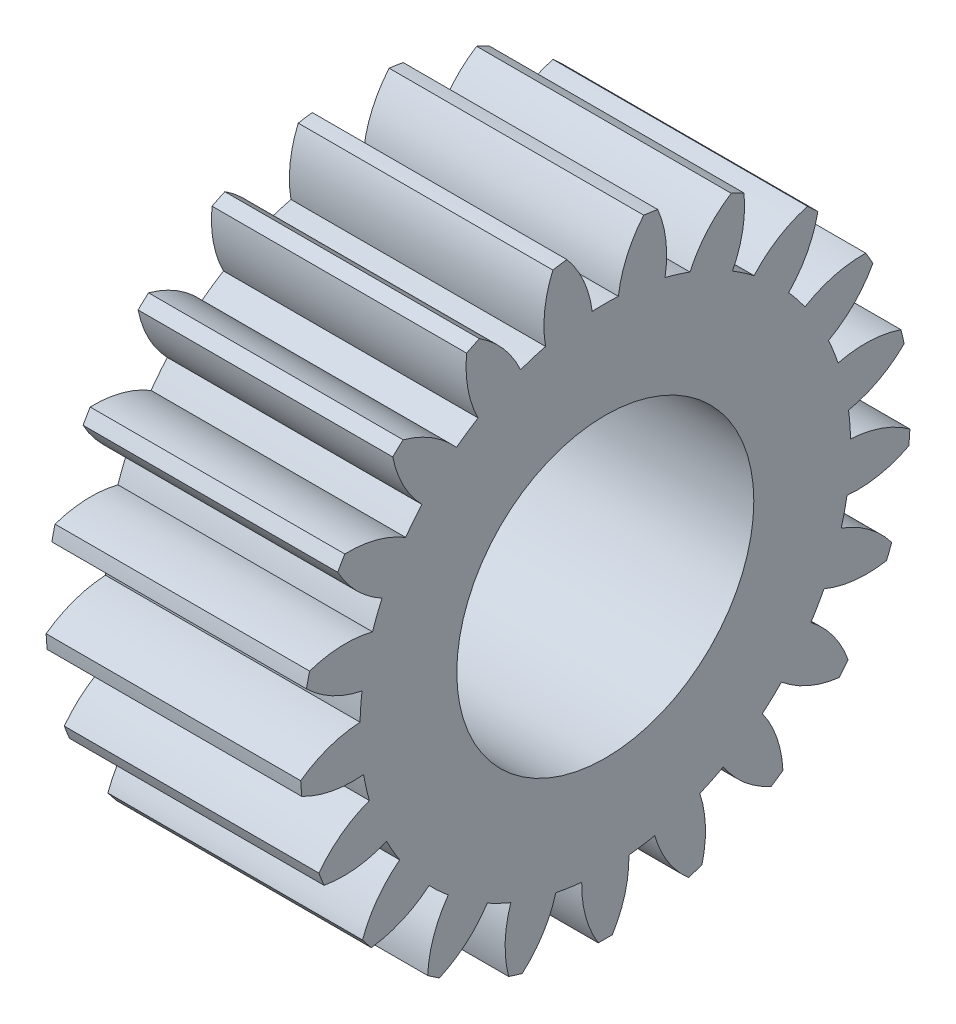
SolidWorks part; units mm, degrees
ref_plane "Plane1" through (0, 0, 0) normal (0, 0, 1) x (1, 0, 0)
ref_plane "Plane2" through (0, 0, 0) normal (0, 1, 0) x (1, 0, 0)
ref_plane "Plane3" through (0, 0, 0) normal (1, 0, 0) x (0, 0, -1)
other "Configuration Table"
sketch "HoldingSke" plane through (0, 0, 0) normal (0, 1, 0) x (1, 0, 0)
  line L0 (0, 0) -> (0.7469, -0.2867)
  line L1 (-15, 0) -> (100, 0) construction
  line L2 (0, 0) -> (-2.1039, 2.3779)
  line L3 (0, 0) -> (-11.863, 4.5341)
  line L4 (0, 0) -> (8.0624, 3.0949)
  line L5 (0, 0) -> (-46.8476, -17.4728)
  line L6 (0, 0) -> (-9.9476, -6.7116)
  line L7 (-2.1039, 2.3779) -> (8.6586, 51.2059)
  line L8 (-76.2, 54.61) -> (-73.9, 54.61)
  line L9 (-71.009, 38.7566) -> (-53.1078, 45.2721)
  line L10 (-76.2, 71.12) -> (104.1128, 71.12)
  line L11 (0, 0) -> (-12, 0)
  line L12 (-76.2, 101.6) -> (-76.155, 101.6)
  line L13 (24.9733, 27.94) -> (52.9518, 28.4284)
  line L14 (24.9733, 27.94) -> (24.9743, 27.94)
  line L15 (24.9733, 27.94) -> (100.4006, 29.5858)
  line L16 (-63.627, -1.25) -> (-12.827, -1.25)
  circle A0 centre (0, 0) radius 7
  circle A1 centre (0, 0) radius 11.5615
  circle A2 centre (0, 0) radius 37.5
  circle A3 centre (0, 0) radius 7
  dimension "MHD" = 23.123
  dimension "Hub_dia" = 75
  dimension "Bore" = 14
  dimension "MBD" = 14
  dimension "Num_teeth" = 21
  dimension "Pitch" = 0.8
  dimension "Overall_len" = 50
  dimension "Show_teeth" = 21
  dimension "Thickness" = 12
  dimension "OAL" = 50.0001
  dimension "T_dim" = 2.3
  dimension "Ap" = 20
  dimension "H" = 19.05
  dimension "Pitch_radius" = 180.3128
  dimension "Width" = 12
  dimension "Backlash" = 0.045
  dimension "Addendum_fac" = 1
  dimension "Dedendum_fac" = 1.25
  dimension "Clearance_fac" = 0.25
  dimension "Dedendum_add" = 0.001
  dimension "Module" = 1.25
sketch "BasProSke" plane through (0, 0, 0) normal (0, 1, 0) x (1, 0, 0)
  line L0 (-10, 0) -> (60, 0) construction
  line L1 (0, 0) -> (0, 14.375)
  line L2 (0, 0) -> (12, 0)
  line L3 (12, 0) -> (12, 14.375)
  line L4 (12, 14.375) -> (0, 14.375)
  dimension "Thickness" = 12
  dimension "Diameter" = 28.75
revolve "Base-Revolve" add sketch "BasProSke" angle 360 about L0
sketch "TooCutSke" plane through (0, 0, 0) normal (1, 0, 0) x (0, 0, -1)
  line L1 (0, 0) -> (0, 107) construction
  line L2 (0, 0) -> (-1.0595, 13.0822) construction
  line L3 (0, 0) -> (-3.9031, 25.8954) construction
  line L4 (-1.0595, 13.0822) -> (-1.9516, 12.9477) construction
  arc A0 (0.6153, 11.5451) -> (-0.6153, 11.5451) centre (0, 0) ccw
  arc A1 (1.8309, 14.2835) -> (-1.8309, 14.2835) centre (0, 0) ccw
  circle A2 centre (0, 0) radius 13.125 construction
  circle A3 centre (0, 0) radius 12.3335 construction
  arc A4 (-0.6153, 11.5451) -> (-1.8309, 14.2835) centre (-5.822, 10.8728) ccw
  arc A5 (1.8309, 14.2835) -> (0.6153, 11.5451) centre (5.822, 10.8728) ccw
  dimension "Root_dia" = 23.123
  dimension "Overcut_dia" = 28.8008
  dimension "Pitch_dia" = 26.25
  dimension "Base_dia" = 24.6669
  dimension "Flank_rad" = 5.25
  dimension "Half_ang" = 8.571
  dimension "Half_CT" = 0.9021
extrude "ToothCut" cut sketch "TooCutSke" along normal through all
fillet "Breaks" [suppressed] radius 0.025
fillet "RootFillets" [suppressed] radius 0.3135
pattern_circular "TeethCuts" count 21 every 17.143 about axis through (-10, 0, 0) along (1, 0, 0) of "ToothCut", "RootFillets", "Breaks"
sketch "HubNeaOneSke" plane through (0, 0, 0) normal (-1, 0, 0) x (0, 0, 1)
  circle A0 centre (0, 0) radius 11.5615
  dimension "Diameter" = 23.123
extrude "HubNearOne" [suppressed] add sketch "HubNeaOneSke" along normal blind 38.0001
sketch "HubNeaBotSke" plane through (0, 0, 0) normal (-1, 0, 0) x (0, 0, 1)
  circle A0 centre (0, 0) radius 11.5615
  dimension "Diameter" = 23.123
extrude "HubNearBoth" [suppressed] add sketch "HubNeaBotSke" along normal blind 19
ref_plane "FarPln" through (12, 0, 0) normal (1, 0, 0) x (0, 0, -1)
sketch "HubFarSke" plane through (12, 0, 0) normal (1, 0, 0) x (0, 0, -1)
  circle A0 centre (0, 0) radius 11.5615
  dimension "Diameter" = 23.123
extrude "HubFar" [suppressed] add sketch "HubFarSke" along normal blind 19
sketch "BorSke" plane through (0, 0, 0) normal (1, 0, 0) x (0, 0, -1)
  circle A0 centre (0, 0) radius 7
  dimension "Diameter" = 14
extrude "Bore" cut sketch "BorSke" along normal mid plane 100.0001
sketch "KeySke" plane through (0, 0, 0) normal (1, 0, 0) x (0, 0, -1)
  line L0 (-2.5, 0) -> (-2.5, 9.3)
  line L1 (-2.5, 9.3) -> (2.5, 9.3)
  line L2 (2.5, 9.3) -> (2.5, 0)
  line L3 (0, 0) -> (0, 34) construction
  line L4 (-2.5, 0) -> (2.5, 0)
  dimension "Offset" = 9.3
  dimension "Width" = 5
extrude "Keyway" [suppressed] cut sketch "KeySke" along normal mid plane 100.0001
pattern_circular "Keyway2" [suppressed] count 2 every 90 about axis through (-10, 0, 0) along (1, 0, 0)
equation "' \"Module@HoldingSke\" = 6.35"
equation "' \"Num_teeth@HoldingSke\" = 12"
equation "' \"Ap@HoldingSke\" =  20"
equation "' \"Ap@HoldingSke\" = 20"
equation "' \"Width@HoldingSke\" = 0.5 * 25.4"
equation "' \"Hub_dia@HoldingSke\"= 1 * 25.4"
equation "' \"Hub_dia@HoldingSke\" = 1 * 25.4"
equation "' \"Overall_len@HoldingSke\" = 1.0 * 25.4"
equation "' \"Bore@HoldingSke\" = 0.75 * 25.4"
equation "' \"T_dim@HoldingSke\" = 0.1 * 25.4"
equation "' \"Width@KeySke\" = 0.25 * 25.4"
equation "' \"Show_teeth@HoldingSke\" = 13"
equation "' \"Backlash@HoldingSke\" = 0.009 * 25.4"
equation "' \"Addendum_fac@HoldingSke\" = 1.0"
equation "' \"Dedendum_fac@HoldingSke\" = 1.25"
equation "' \"Dedendum_add@HoldingSke\" = 0.00005 * 25.4"
equation "' \"Clearance_fac@HoldingSke\" = 0.25"
equation "\"Pitch@HoldingSke\" = 1 / \"Module@HoldingSke\""
equation "\"Overcut_dia@TooCutSke\" = (\"Num_teeth@HoldingSke\" + 2 * \"Addendum_fac@HoldingSke\") / \"Pitch@HoldingSke\" + 0.002 * 25.4"
equation "\"Pitch_dia@TooCutSke\" = \"Num_teeth@HoldingSke\" / \"Pitch@HoldingSke\""
equation "\"Base_dia@TooCutSke\" = \"Num_teeth@HoldingSke\" / \"Pitch@HoldingSke\" * cos((\"Ap@HoldingSke\"  * 3.14159265 / 180))"
equation "\"Root_dia@TooCutSke\" = (\"Num_teeth@HoldingSke\" + 2) / \"Pitch@HoldingSke\" - 2 * (\"Addendum_fac@HoldingSke\" + \"Dedendum_fac@HoldingSke\") / \"Pitch@HoldingSke\" - \"Dedendum_add@HoldingSke\" * 2"
equation "\"Half_ang@TooCutSke\" = 180 / \"Num_teeth@HoldingSke\""
equation "\"Half_CT@TooCutSke\" = \"Num_teeth@HoldingSke\" / \"Pitch@HoldingSke\" * sin((3.14159265 / 2 / \"Num_teeth@HoldingSke\")) / 2 - 7 * \"Backlash@HoldingSke\" / 4"
equation "\"Flank_rad@TooCutSke\" = \"Num_teeth@HoldingSke\" / \"Pitch@HoldingSke\" / 5"
equation "\"Radius@RootFillets\" = \"Clearance_fac@HoldingSke\" / \"Pitch@HoldingSke\" + \"Dedendum_add@HoldingSke\""
equation "\"Break_rad@Breaks\" = 0.02 / \"Pitch@HoldingSke\""
equation "\"Thickness@HoldingSke\" = \"Width@HoldingSke\""
equation "\"OAL@HoldingSke\" = \"Thickness@HoldingSke\""
equation "\"MHD@HoldingSke\" = (\"Num_teeth@HoldingSke\" + 2) / \"Pitch@HoldingSke\" - 2 * (\"Addendum_fac@HoldingSke\" + \"Dedendum_fac@HoldingSke\")  / \"Pitch@HoldingSke\" - \"Dedendum_add@HoldingSke\" * 2"
equation "\"MBD@HoldingSke\" = (\"Num_teeth@HoldingSke\" + 2) / \"Pitch@HoldingSke\" - 2 * (\"Addendum_fac@HoldingSke\" + \"Dedendum_fac@HoldingSke\")  / \"Pitch@HoldingSke\" - \"Dedendum_add@HoldingSke\" * 2 - 0.002 * 25.4"
equation "\"MHD@HoldingSke\" = ((sgn( \"MHD@HoldingSke\" - \"Hub_dia@HoldingSke\" )-1)*( \"MHD@HoldingSke\" - \"Hub_dia@HoldingSke\" ))/-2+ \"Hub_dia@HoldingSke\""
equation "\"MBD@HoldingSke\" = ((sgn( \"MBD@HoldingSke\" - \"Bore@HoldingSke\" )-1)*( \"MBD@HoldingSke\" - \"Bore@HoldingSke\" ))/-2+ \"Bore@HoldingSke\""
equation "\"OAL@HoldingSke\" = ((sgn( \"OAL@HoldingSke\" - \"Overall_len@HoldingSke\" )+1)*( \"OAL@HoldingSke\" - \"Overall_len@HoldingSke\" ))/2 + \"Overall_len@HoldingSke\" + 0.000002 * 25.4"
equation "\"Num_teeth@TeethCuts\" = int( \"Show_teeth@HoldingSke\" ) + 1"
equation "\"Num_teeth@TeethCuts\" = ((sgn( \"Num_teeth@TeethCuts\" - \"Num_teeth@HoldingSke\" )-1)*( \"Num_teeth@TeethCuts\" - \"Num_teeth@HoldingSke\" ))/-2+ \"Num_teeth@HoldingSke\""
equation "\"Num_teeth@TeethCuts\" = ((sgn( \"Num_teeth@TeethCuts\" - 2.0)+1)*( \"Num_teeth@TeethCuts\" - 2.0))/2 +2.0"
equation "\"Angle@TeethCuts\" = 360.0 / \"Num_teeth@HoldingSke\""
equation "\"Diameter@BasProSke\" = (\"Num_teeth@HoldingSke\" + 2 * \"Addendum_fac@HoldingSke\") / \"Pitch@HoldingSke\""
equation "\"Thickness@BasProSke\"  = \"Thickness@HoldingSke\""
equation "' \"Fillet_rad@BasProSke\" =  \"Thickness@HoldingSke\" * 0.05"
equation "' \"Fillet_rad@BasProSke\" = \"Thickness@HoldingSke\" * 0.05"
equation "\"MHD@HoldingSke\" = ((sgn( \"MHD@HoldingSke\" - \"Root_dia@TooCutSke\" )-1)*( \"MHD@HoldingSke\" - \"Root_dia@TooCutSke\" ))/-2+ \"Root_dia@TooCutSke\""
equation "\"Diameter@HubNeaOneSke\" = \"MHD@HoldingSke\""
equation "\"Length@HubNearOne\" = \"OAL@HoldingSke\" - \"Thickness@BasProSke\""
equation "\"Diameter@HubNeaBotSke\" = \"MHD@HoldingSke\""
equation "\"Length@HubNearBoth\" = ( \"OAL@HoldingSke\" - \"Thickness@BasProSke\" ) / 2.0"
equation "\"Thickness@FarPln\" = \"Thickness@BasProSke\""
equation "\"Diameter@HubFarSke\" = \"MHD@HoldingSke\""
equation "\"Length@HubFar\" = ( \"OAL@HoldingSke\" - \"Thickness@BasProSke\" ) / 2.0"
equation "\"Diameter@BorSke\" = \"MBD@HoldingSke\""
equation "\"D1@Bore\" = \"OAL@HoldingSke\" * 2.0"
equation "\"D1@Keyway\" = \"OAL@HoldingSke\" * 2.0"
equation "\"Offset@KeySke\" = \"T_dim@HoldingSke\" + \"MBD@HoldingSke\" / 2.0"
